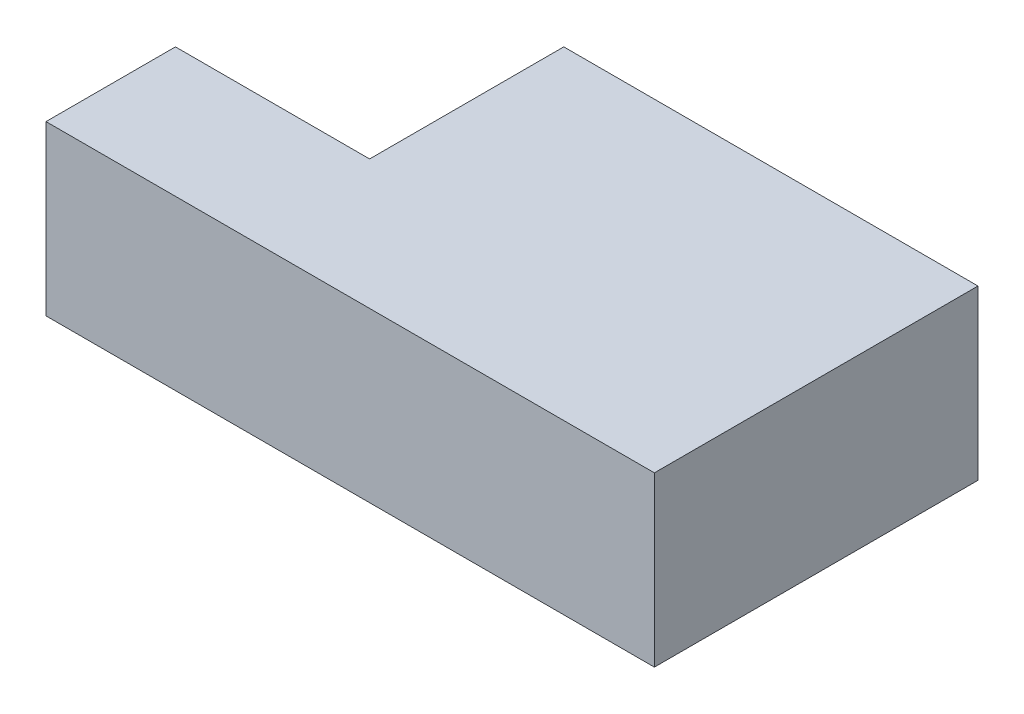
SolidWorks part; units mm, degrees
ref_plane "前视基准面" through (0, 0, 0) normal (0, 0, 1) x (1, 0, 0)
ref_plane "上视基准面" through (0, 0, 0) normal (0, 1, 0) x (1, 0, 0)
ref_plane "右视基准面" through (0, 0, 0) normal (1, 0, 0) x (0, 0, -1)
sketch "草图1" plane through (0, 0, 0) normal (0, 1, 0) x (1, 0, 0)
  line L0 (0, 0) -> (0, 25)
  line L1 (0, 25) -> (-32, 25)
  line L2 (-32, 25) -> (-32, 10)
  line L3 (-32, 10) -> (-47, 10)
  line L4 (-47, 10) -> (-47, 0)
  line L5 (-47, 0) -> (0, 0)
  dimension "D1" = 15
  dimension "D2" = 15
  dimension "D3" = 32
  dimension "D4" = 10
extrude "凸台-拉伸1" add sketch "草图1" along normal blind 13
sketch "草图2" plane through (0, 0, 0) normal (0, -1, 0) x (1, 0, 0)
  line L12 (-2, -2) -> (-45, -2)
  line L13 (-45, -2) -> (-45, -8)
  line L14 (-45, -8) -> (-30, -8)
  line L15 (-30, -8) -> (-30, -23)
  line L16 (-30, -23) -> (-2, -23)
  line L17 (-2, -23) -> (-2, -2)
  line L18 (-2, -2) -> (-45, -2)
  line L19 (-45, -2) -> (-45, -8)
  line L20 (-45, -8) -> (-30, -8)
  line L21 (-30, -8) -> (-30, -23)
  line L22 (-30, -23) -> (-2, -23)
  line L23 (-2, -23) -> (-2, -2)
  dimension "D1" = 2
extrude "切除-拉伸1" cut sketch "草图2" against normal offset from surface (11 mm away) 2 up to face at (-26.3333, 13, -11.6667)
